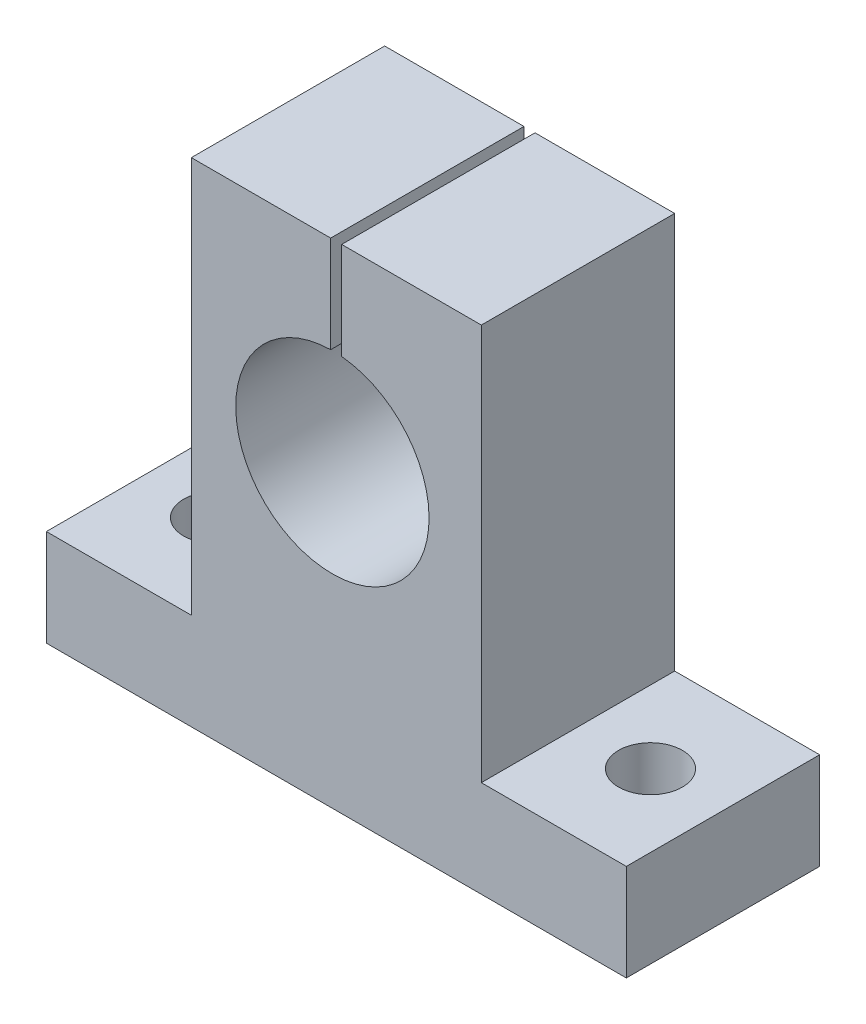
SolidWorks part; units mm, degrees
material "Nickel"
ref_plane "Front Plane" through (0, 0, 0) normal (0, 0, 1) x (1, 0, 0)
ref_plane "Top Plane" through (0, 0, 0) normal (0, 1, 0) x (1, 0, 0)
ref_plane "Right Plane" through (0, 0, 0) normal (1, 0, 0) x (0, 0, -1)
sketch "Sketch1" plane through (0, 0, 0) normal (0, 0, 1) x (1, 0, 0)
  line L1 (-642.6877, 383.004) -> (-582.6877, 383.004)
  line L2 (-642.6877, 383.004) -> (-642.6877, 332.004)
  line L3 (-642.6877, 332.004) -> (-582.6877, 332.004)
  line L4 (-582.6877, 383.004) -> (-582.6877, 332.004)
  dimension "D1" = 60
  dimension "D2" = 51
extrude "Boss-Extrude1" add sketch "Sketch1" along normal blind 20
sketch "Sketch2" plane through (0, 0, 20) normal (0, 0, 1) x (1, 0, 0)
  line L1 (-642.6877, 383.004) -> (-627.6877, 383.004)
  line L2 (-642.6877, 383.004) -> (-642.6877, 342.004)
  line L3 (-642.6877, 342.004) -> (-627.6877, 342.004)
  line L4 (-627.6877, 383.004) -> (-627.6877, 342.004)
  line L6 (-582.6877, 383.004) -> (-582.6877, 342.004)
  line L7 (-582.6877, 342.004) -> (-597.6877, 342.004)
  line L8 (-597.6877, 383.004) -> (-597.6877, 342.004)
  line L9 (-582.6877, 383.004) -> (-597.6877, 383.004)
  dimension "D1" = 41
  dimension "D2" = 15
extrude "Cut-Extrude1" cut sketch "Sketch2" against normal blind 20
sketch "Sketch3" plane through (0, 0, 20) normal (0, 0, 1) x (1, 0, 0)
  line L0 (-613.095, 383.004) -> (-613.095, 363.004) construction
  line L1 (-597.6877, 383.004) -> (-627.6877, 383.004) construction
  circle A0 centre (-613.095, 363.004) radius 10
  dimension "D2" = 20
  dimension "D1" = 20
extrude "Cut-Extrude2" cut sketch "Sketch3" against normal blind 20
sketch "Sketch4" plane through (0, 342.004, 0) normal (0, 1, 0) x (1, 0, 0)
  line L0 (-642.6877, -10) -> (-582.6877, -10) construction
  line L1 (-642.6877, 0) -> (-642.6877, -20) construction
  line L2 (-582.6877, 0) -> (-582.6877, -20) construction
  line L3 (-635.1877, 0) -> (-635.1877, -20) construction
  line L4 (-642.6877, 0) -> (-627.6877, 0) construction
  line L5 (-642.6877, -20) -> (-627.6877, -20) construction
  line L6 (-590.1877, 0) -> (-590.1877, -20) construction
  line L7 (-597.6877, 0) -> (-582.6877, 0) construction
  line L8 (-597.6877, -20) -> (-582.6877, -20) construction
  circle A0 centre (-635.1877, -10) radius 3.3
  circle A1 centre (-590.1877, -10) radius 3.3
  dimension "D1" = 6.6
  dimension "D2" = 6.6
extrude "Cut-Extrude3" cut sketch "Sketch4" against normal blind 20
sketch "Sketch7" plane through (0, 0, 20) normal (0, 0, 1) x (1, 0, 0)
  line L0 (-612.6877, 383.004) -> (-612.6877, 372.9957) construction
  line L1 (-597.6877, 383.004) -> (-627.6877, 383.004) construction
  line L3 (-613.2743, 383.004) -> (-612.1325, 383.004)
  line L4 (-613.2743, 383.004) -> (-613.2743, 372.9575)
  line L5 (-613.2743, 372.9575) -> (-612.1325, 372.9575)
  line L6 (-612.1325, 383.004) -> (-612.1325, 372.9575)
  circle A0 centre (-613.095, 363.004) radius 10 construction
extrude "Cut-Extrude4" cut sketch "Sketch7" against normal blind 20
scale "Scale1" bodies to scale 105 scale about centroid uniform scaling yes scale factor 0.8
scale "Scale2" bodies to scale 106 scale about centroid uniform scaling yes scale factor 0.5
